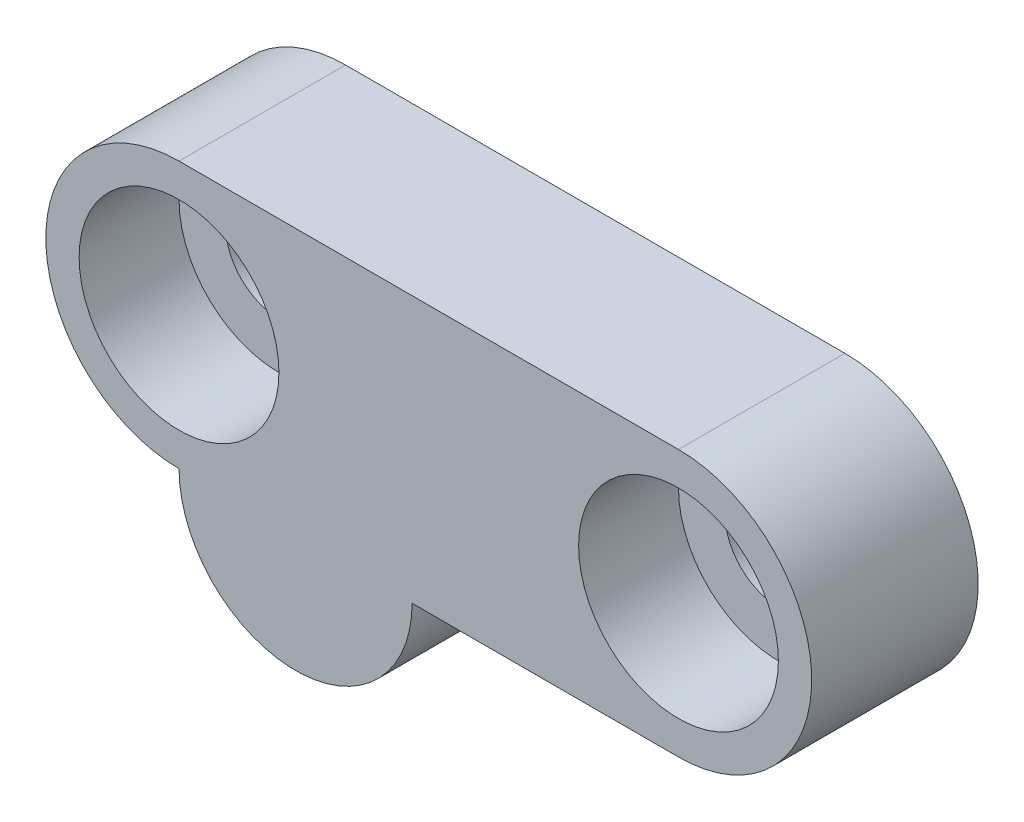
SolidWorks part; units mm, degrees
material "ABS"
ref_plane "Front Plane" through (0, 0, 0) normal (0, 0, 1) x (1, 0, 0)
ref_plane "Top Plane" through (0, 0, 0) normal (0, 1, 0) x (1, 0, 0)
ref_plane "Right Plane" through (0, 0, 0) normal (1, 0, 0) x (0, 0, -1)
sketch "Sketch1" plane through (0, 0, 22) normal (0, 0, 1) x (1, 0, 0)
  line L0 (0, 0) -> (15, 0) construction
  line L1 (0, 4) -> (15, 4)
  line L3 (7, -4) -> (15, -4)
  line L4 (0, -4) -> (7, -4) construction
  arc A0 (0, 4) -> (0, -4) centre (0, 0) ccw
  arc A1 (15, -4) -> (15, 4) centre (15, 0) ccw
  circle A2 centre (0, 0) radius 1.6
  circle A3 centre (15, 0) radius 1.6
  arc A4 (0, -4) -> (7, -4) centre (3.5, -4) ccw
extrude "Boss-Extrude1" add sketch "Sketch1" along normal blind 5
sketch "Sketch2" plane through (0, 0, 27) normal (0, 0, 1) x (1, 0, 0)
  circle A0 centre (0, 0) radius 3
  circle A1 centre (15, 0) radius 3
  dimension "D1" = 6
  dimension "D2" = 6
extrude "Cut-Extrude1" cut sketch "Sketch2" against normal blind 3
